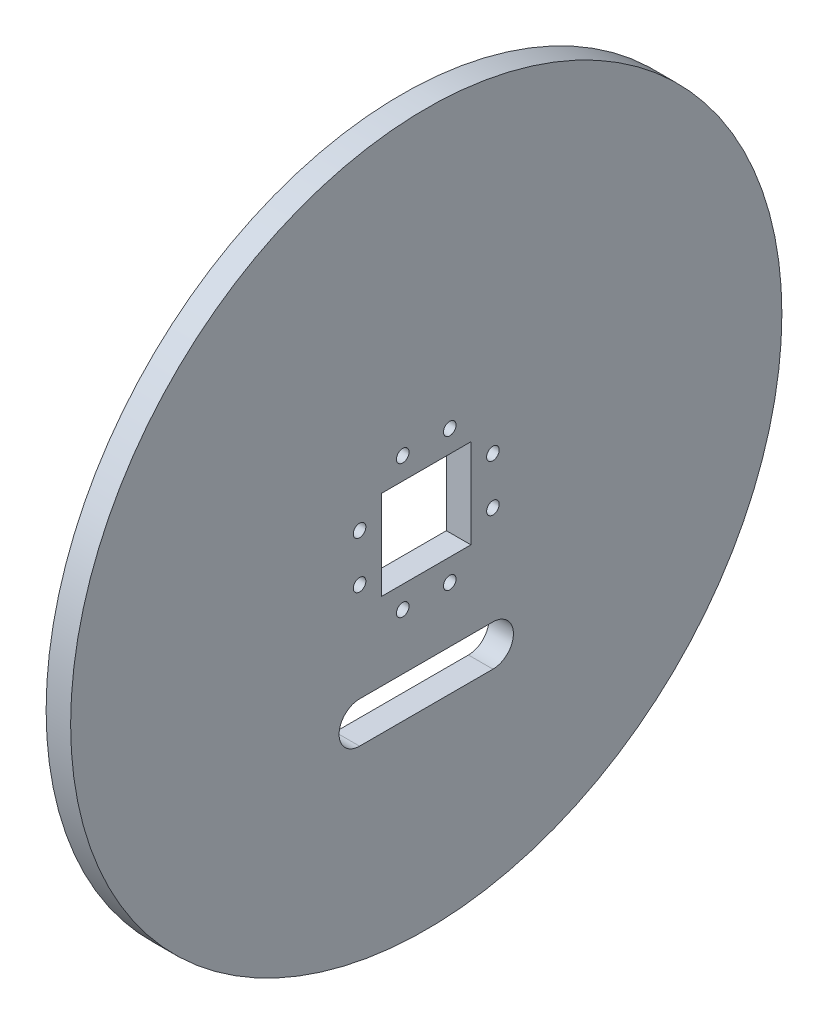
SolidWorks part; units mm, degrees
ref_plane "Front Plane" through (0, 0, 0) normal (0, 0, 1) x (1, 0, 0)
ref_plane "Top Plane" through (0, 0, 0) normal (0, 1, 0) x (1, 0, 0)
ref_plane "Right Plane" through (0, 0, 0) normal (1, 0, 0) x (0, 0, -1)
sketch "Sketch1" plane through (0, 0, 0) normal (1, 0, 0) x (0, 0, -1)
  line L0 (-19.05, -40.8077) -> (19.05, -40.8077) construction
  line L1 (-12.75, -12.75) -> (12.75, -12.75)
  line L2 (-12.75, -12.75) -> (-12.75, 12.75)
  line L3 (-12.75, 12.75) -> (12.75, 12.75)
  line L4 (12.75, -12.75) -> (12.75, 12.75)
  line L5 (-12.75, -12.75) -> (12.75, 12.75) construction
  line L6 (-12.75, 12.75) -> (12.75, -12.75) construction
  line L7 (-19.05, -34.9619) -> (19.05, -34.9619)
  line L8 (-19.05, -46.6534) -> (19.05, -46.6534)
  circle A0 centre (0, 0) radius 101.6
  arc A1 (-19.05, -34.9619) -> (-19.05, -46.6534) centre (-19.05, -40.8077) ccw
  arc A2 (19.05, -46.6534) -> (19.05, -34.9619) centre (19.05, -40.8077) ccw
  circle A3 centre (19.05, 6.7184) radius 1.8
  circle A4 centre (0, 0) radius 20.2 construction
  circle A5 centre (19.05, -6.7184) radius 1.8
  circle A6 centre (-6.7184, -19.05) radius 1.8
  circle A7 centre (6.7184, -19.05) radius 1.8
  circle A8 centre (-19.05, 6.7184) radius 1.8
  circle A9 centre (-19.05, -6.7184) radius 1.8
  circle A10 centre (6.7184, 19.05) radius 1.8
  circle A11 centre (-6.7184, 19.05) radius 1.8
  point P9 (0, -40.8077)
  point P35 (0, 0)
  dimension "D1" = 4
extrude "Boss-Extrude2" add sketch "Sketch1" along normal blind 7
